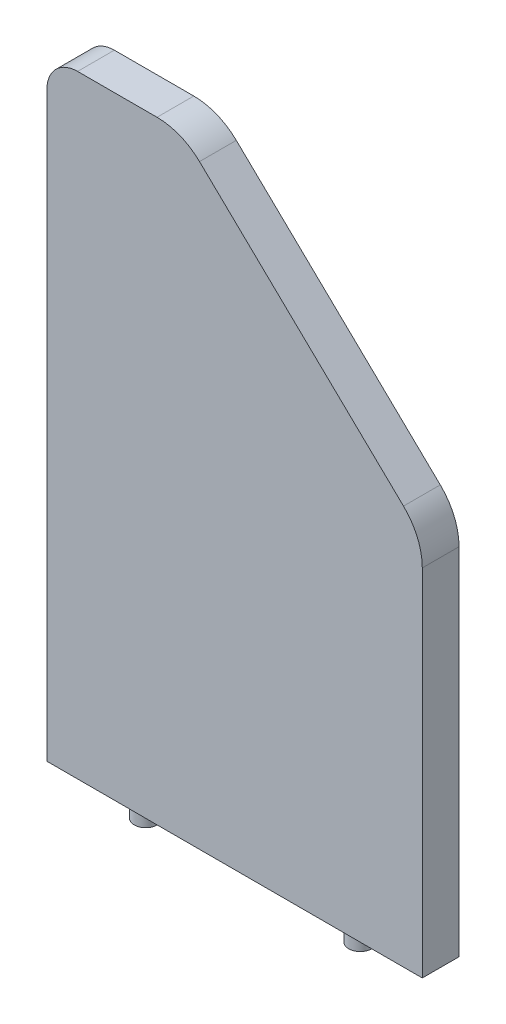
SolidWorks part; units mm, degrees
ref_plane "Front Plane" through (0, 0, 0) normal (0, 0, 1) x (1, 0, 0)
ref_plane "Top Plane" through (0, 0, 0) normal (0, 1, 0) x (1, 0, 0)
ref_plane "Right Plane" through (0, 0, 0) normal (1, 0, 0) x (0, 0, -1)
sketch "Sketch4" plane through (0, 0, 0) normal (0, 0, 1) x (1, 0, 0)
  line L1 (0, 0) -> (122.5, 0)
  line L2 (0, 0) -> (0, 200)
  line L3 (0, 200) -> (122.5, 200)
  line L4 (122.5, 0) -> (122.5, 200)
  dimension "D1" = 122.5
  dimension "D2" = 200
extrude "Boss-Extrude1" add sketch "Sketch4" along normal blind 12
sketch "Sketch7" plane through (0, 0, 12) normal (0, 0, 1) x (1, 0, 0)
  line L1 (122.5, 200) -> (0, 200) construction
  line L2 (43.9858, 200) -> (122.5, 124.4158)
  line L3 (122.5, 0) -> (122.5, 200) construction
  line L4 (43.9858, 200) -> (122.5, 200)
  line L5 (122.5, 200) -> (122.5, 124.4158)
extrude "Cut-Extrude1" cut sketch "Sketch7" against normal blind 12
fillet "Fillet1" radius 20 1 edges at (43.9858, 200, 6)
fillet "Fillet2" radius 20 1 edges at (122.5, 124.4158, 6)
fillet "Fillet3" radius 10 1 edges at (0, 200, 6)
sketch "Sketch10" plane through (0, 0, 0) normal (0, -1, 0) x (1, 0, 0)
  circle A0 centre (26.25, 6) radius 3.75
  circle A1 centre (96.25, 6) radius 3.75
extrude "Boss-Extrude3" add sketch "Sketch10" along normal blind 6
sketch "Sketch11" plane through (0, -6, 0) normal (0, -1, 0) x (1, 0, 0)
  circle A0 centre (26.25, 6) radius 3.75
  circle A1 centre (96.25, 6) radius 3.75
extrude "Boss-Extrude4" add sketch "Sketch11" along normal blind 2 draft 62
sketch "Sketch12" plane through (0, 0, 0) normal (-1, 0, 0) x (0, 0, 1)
  line L0 (12, 0) -> (12, 10)
  line L1 (0, 190) -> (0, 0) construction
  line L2 (0, 180) -> (12, 180)
  line L3 (12, 190) -> (12, 0) construction
  line L4 (6, 190) -> (6, 180)
  line L5 (12, 190) -> (0, 190) construction
  line L6 (12, 10) -> (6, 10)
  line L7 (6, 10) -> (6, 0)
  line L8 (12, 0) -> (0, 0) construction
hole_wizard "Ø5.0 (5) Diameter Hole1" positions "Sketch14" profile "Sketch13" hole size "Ø5.0" standard "ANSI Metric"
sketch "Sketch14" plane through (0, 0, 0) normal (-1, 0, 0) x (0, 0, 1)
  point P0 (6, 180)
sketch "Sketch13" plane through (0, 180, 6) normal (0, 1, 0) x (0, 0, 1)
  line L0 (0, 0) -> (0, 9.5022)
  line L1 (0, 9.5022) -> (2.5, 8)
  line L2 (2.5, 8) -> (2.5, 0)
  line L5 (2.5, 0) -> (0, 0)
  line L10 (0, 9.5022) -> (-2.5, 8) construction
  line L11 (0, -6.35) -> (0, 107.95) construction
  dimension "Hole Dia." = 5
  dimension "Hole Depth" = 8
  dimension "Drill Angle" = 118
hole_wizard "Ø5.0 (5) Diameter Hole2" positions "Sketch17" profile "Sketch16" hole size "Ø5.0" standard "ANSI Metric"
sketch "Sketch17" plane through (0, 0, 0) normal (-1, 0, 0) x (0, 0, 1)
  point P0 (6, 10)
sketch "Sketch16" plane through (0, 10, 6) normal (0, 1, 0) x (0, 0, 1)
  line L0 (0, 0) -> (0, 9.5022)
  line L1 (0, 9.5022) -> (2.5, 8)
  line L2 (2.5, 8) -> (2.5, 0)
  line L5 (2.5, 0) -> (0, 0)
  line L10 (0, 9.5022) -> (-2.5, 8) construction
  line L11 (0, -6.35) -> (0, 107.95) construction
  dimension "Hole Dia." = 5
  dimension "Hole Depth" = 8
  dimension "Drill Angle" = 118
